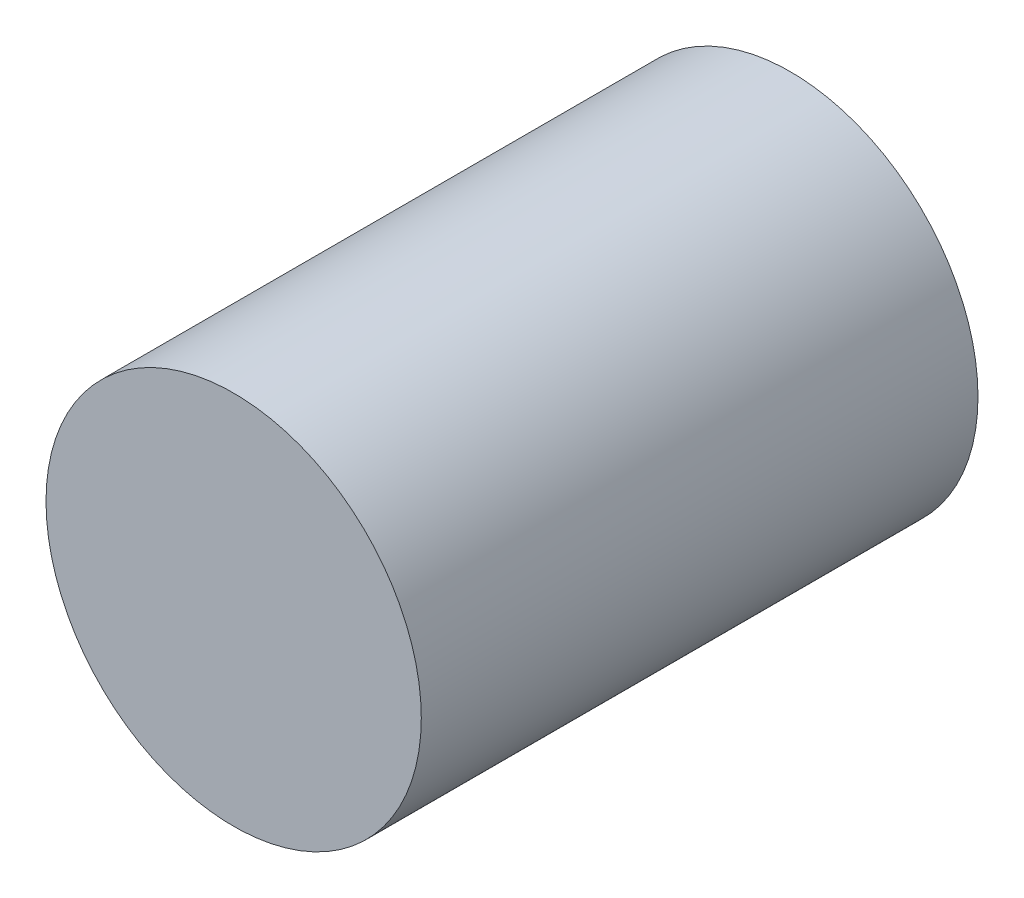
SolidWorks part; units mm, degrees
ref_plane "Front Plane" through (0, 0, 0) normal (0, 0, 1) x (1, 0, 0)
ref_plane "Top Plane" through (0, 0, 0) normal (0, 1, 0) x (1, 0, 0)
ref_plane "Right Plane" through (0, 0, 0) normal (1, 0, 0) x (0, 0, -1)
sketch "Sketch1" plane through (0, 0, 0) normal (0, 0, 1) x (1, 0, 0)
  circle A0 centre (0, 0) radius 60
  dimension "D1" = 120
extrude "Boss-Extrude1" add sketch "Sketch1" against normal blind 178
